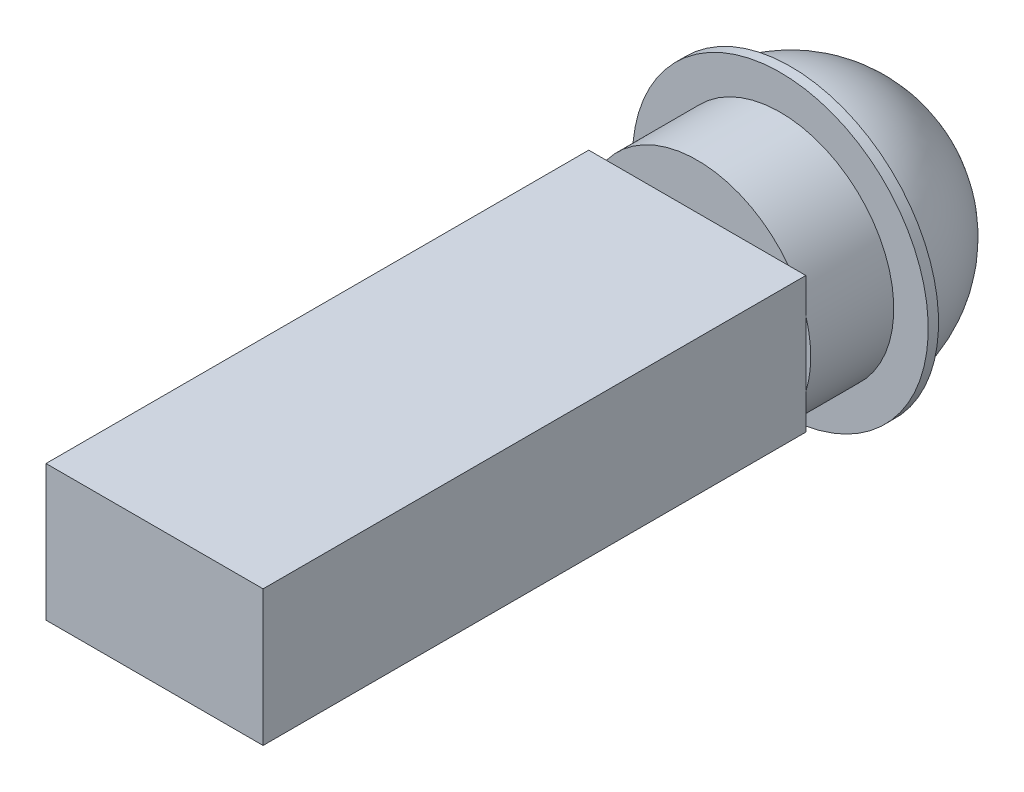
SolidWorks part; units mm, degrees
ref_plane "Front Plane" through (0, 0, 0) normal (0, 0, 1) x (1, 0, 0)
ref_plane "Top Plane" through (0, 0, 0) normal (0, 1, 0) x (1, 0, 0)
ref_plane "Right Plane" through (0, 0, 0) normal (1, 0, 0) x (0, 0, -1)
sketch "Sketch1" plane through (0, 0, 0) normal (0, 1, 0) x (1, 0, 0)
  line L0 (0, 6.2039) -> (0, -4.3688)
  line L1 (0, -4.3688) -> (-5.3086, -4.3688)
  line L2 (-5.3086, -4.3688) -> (-5.3086, -0.4826)
  line L3 (-5.3086, -0.4826) -> (-6.9215, -0.4826)
  line L4 (-6.9215, -0.4826) -> (-6.9215, 0)
  line L5 (-6.9215, 0) -> (-6.2039, 0)
  line L6 (0, 6.2039) -> (13.3606, 6.2039) construction
  arc A0 (-6.2039, 0) -> (0, 6.2039) centre (0, 0) cw
  dimension "D1" = 0.4826
  dimension "D2" = 6.9215
  dimension "D3" = 6.2039
  dimension "D4" = 5.3086
  dimension "D5" = 3.8862
revolve "Revolve1" add sketch "Sketch1" angle 360 about L0
sketch "Sketch2" plane through (0, 0, 4.3688) normal (0, 0, 1) x (1, 0, 0)
  line L1 (5.08, 3.175) -> (-5.08, 3.175)
  line L2 (5.08, 3.175) -> (5.08, -3.175)
  line L3 (5.08, -3.175) -> (-5.08, -3.175)
  line L4 (-5.08, 3.175) -> (-5.08, -3.175)
  line L5 (5.08, 3.175) -> (-5.08, -3.175) construction
  line L6 (5.08, -3.175) -> (-5.08, 3.175) construction
  point P0 (0, 0)
  dimension "D1" = 10.16
  dimension "D2" = 6.35
extrude "Boss-Extrude1" add sketch "Sketch2" along normal blind 25.4
